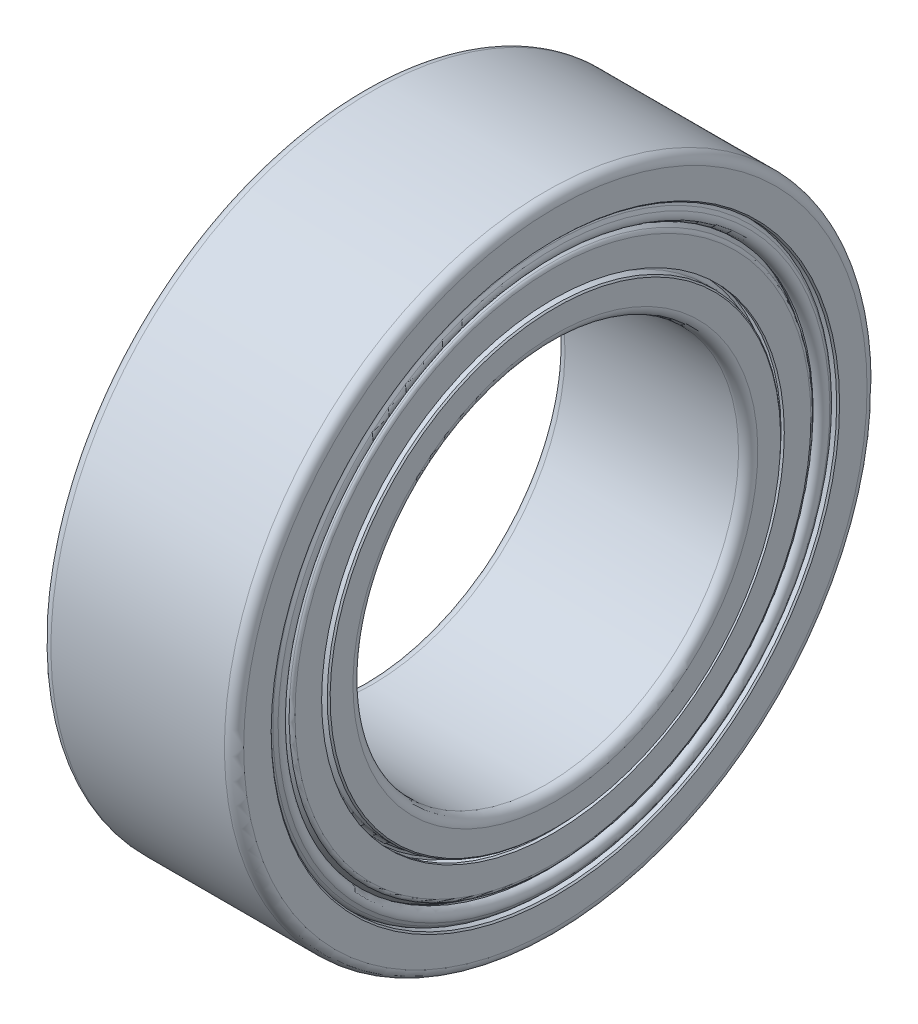
SolidWorks part; units mm, degrees
ref_plane "Front Plane" through (0, 0, 0) normal (0, 0, 1) x (1, 0, 0)
ref_plane "Top Plane" through (0, 0, 0) normal (0, 1, 0) x (1, 0, 0)
ref_plane "Right Plane" through (0, 0, 0) normal (1, 0, 0) x (0, 0, -1)
sketch "Sketch1" plane through (0, 0, 0) normal (1, 0, 0) x (0, 0, -1)
  line L0 (0, 5) -> (0, 4.85) construction
  line L1 (0, 3) -> (0, 3.15) construction
  circle A0 centre (0, 0) radius 5
  circle A1 centre (0, 0) radius 3
  circle A2 centre (0, 0) radius 4.4 construction
  circle A3 centre (0, 0) radius 3.6 construction
  dimension "OD | For Housing ID" = 10
  dimension "ID | For Shaft Diameter" = 6
  dimension "Outer Ring ID" = 8.8
  dimension "Inner Ring OD" = 7.2
  dimension "Radius" = 0.15
sketch "Sketch2" plane through (0, 0, 0) normal (0, 0, 1) x (1, 0, 0)
  line L0 (-1.5, 5) -> (1.5, 5) construction
  point P3 (0, 5)
  dimension "Width" = 3
sketch "Sketch3" plane through (0, 0, 0) normal (0, 0, 1) x (1, 0, 0)
  line L0 (-1.35, 5) -> (1.35, 5)
  line L1 (-1.5, 4.85) -> (-1.5, 4.4225)
  line L2 (1.5, 4.85) -> (1.5, 4.4225)
  line L3 (-1.4775, 4.4) -> (-1.275, 4.4)
  line L4 (-1.4775, 3.5276) -> (-1.5, 3.5051)
  line L5 (-1.3418, 3.5276) -> (-1.4775, 3.5276)
  line L6 (1.5, 4.4225) -> (1.4775, 4.4)
  line L7 (0, 5) -> (0, 4.4) construction
  line L8 (-1.5, 4.4225) -> (-1.4775, 4.4)
  line L9 (1.4775, 3.5276) -> (1.4775, 3.6) construction
  line L10 (-1.2469, 3.6) -> (-1.2469, 3.636)
  line L11 (-1.35, 3) -> (1.35, 3)
  line L12 (-1.5, 3.15) -> (-1.5, 3.5051)
  line L13 (1.5, 3.15) -> (1.5, 3.5051)
  line L14 (-1.2469, 3.6) -> (1.2469, 3.6) construction
  line L15 (1.2469, 3.6) -> (1.2469, 3.45) construction
  line L16 (1.2469, 3.45) -> (1.2469, 3.3) construction
  line L17 (1.2469, 3.6) -> (1.2469, 3.5276) construction
  line L18 (1.2469, 3.5276) -> (1.4775, 3.5276) construction
  line L19 (1.4775, 3.5276) -> (1.5, 3.5051)
  line L20 (1.3418, 3.5276) -> (1.4775, 3.5276)
  line L21 (1.2469, 3.3) -> (1.2469, 3.15) construction
  line L22 (-1.35, 0) -> (1.35, 0) construction
  line L23 (1.275, 4.4) -> (1.275, 4.436)
  line L24 (1.275, 4.436) -> (-1.275, 4.436)
  line L25 (-1.275, 4.4) -> (-1.275, 4.436)
  line L26 (1.275, 4.4) -> (1.4775, 4.4)
  line L27 (-1.2469, 3.636) -> (1.2469, 3.636)
  line L28 (1.2469, 3.636) -> (1.2469, 3.6)
  arc A0 (-1.5, 4.85) -> (-1.35, 5) centre (-1.35, 4.85) cw
  arc A1 (1.35, 5) -> (1.5, 4.85) centre (1.35, 4.85) cw
  arc A2 (-1.5, 3.15) -> (-1.35, 3) centre (-1.35, 3.15) ccw
  arc A3 (1.35, 3) -> (1.5, 3.15) centre (1.35, 3.15) ccw
  arc A4 (1.2469, 3.6) -> (1.3418, 3.5276) centre (1.3418, 3.626) ccw
  arc A5 (-1.2469, 3.6) -> (-1.3418, 3.5276) centre (-1.3418, 3.626) cw
  point P7 (-1.5, 5)
  point P15 (1.5, 5)
  point P30 (0, 3.6)
  point P48 (0, 4.436)
  dimension "D1" = 0.15
  dimension "D4" = 0.15
  dimension "D2" = 135
  dimension "D3" = 0.0225
  dimension "D5" = 135
  dimension "D7" = 0.2531
  dimension "D9" = 0.036
  dimension "D10" = 0.225
  dimension "D8" = 0.0949
  dimension "D6" = 0.0949
revolve "Revolve1" add sketch "Sketch3" angle 360 about L22
sketch "Sketch4" plane through (0, 0, 0) normal (0, 0, 1) x (1, 0, 0)
  line L6 (1.3525, 4.1861) -> (1.33, 4.1991) construction
  line L7 (1.2925, 4.29) -> (1.2925, 4.1601)
  line L8 (1.3, 4.1471) -> (1.4288, 4.0728)
  line L9 (1.4625, 4.0143) -> (1.4625, 3.6)
  line L10 (1.5, -4.85) -> (1.5, 4.85) construction
  line L11 (1.4625, 3.6) -> (1.4025, 3.6) construction
  line L12 (1.4425, 4.238) -> (1.4625, 4.238) construction
  line L15 (1.33, 4.1991) -> (1.3, 4.1471) construction
  line L18 (1.4045, 4.32) -> (1.4345, 4.268)
  line L20 (1.275, 4.4) -> (1.4775, 4.4) construction
  arc A0 (1.2925, 4.29) -> (1.4045, 4.32) centre (1.3525, 4.29) cw
  arc A1 (1.4345, 4.268) -> (1.3525, 4.1861) centre (1.3825, 4.238) cw construction
  arc A2 (1.4288, 4.0728) -> (1.4625, 4.0143) centre (1.395, 4.0143) cw
  arc A3 (1.2925, 4.1601) -> (1.3, 4.1471) centre (1.3075, 4.1601) ccw
  arc A4 (1.4345, 4.268) -> (1.3825, 4.178) centre (1.3825, 4.238) cw
  point P18 (1.2469, 3.6)
  point P28 (1.4625, 4.0533)
  point P31 (1.2925, 4.1514)
  dimension "D8" = 0.0675
  dimension "D9" = 0.015
  dimension "D6" = 0.06
  dimension "D1" = 0.0375
  dimension "D3" = 0.06
  dimension "D2" = 0.06
  dimension "D7" = 30
  dimension "D4" = 120
  dimension "D12" = 0.02
  dimension "D5" = 0.05
revolve "Revolve-Thin1" add sketch "Sketch4" angle 360 about L22
mirror "Mirror2" about plane through (0, 0, 0) normal (1, 0, 0) of bodies 106
delete or keep bodies "Body-Delete/Keep 1" type delete bodies bodies 113
mirror "Mirror1" about plane through (0, 0, 0) normal (1, 0, 0) of bodies 106 112
equation "\"D4@Sketch3\"=\"D1@Sketch3\""
equation "\"D1@Sketch3\"=\"Radius@Sketch1\""
equation "\"D8@Sketch4\"=\"D3@Sketch4\"*1.125"
equation "\"D9@Sketch4\"=\"D3@Sketch4\"*.25"
equation "\"Outer Ring ID@Sketch1\"=\"OD | For Housing ID@Sketch1\"-(((\"OD | For Housing ID@Sketch1\"-\"ID | For Shaft Diameter@Sketch1\")/2)*.3*2)"
equation "\"Inner Ring OD@Sketch1\"=\"ID | For Shaft Diameter@Sketch1\"+(((\"OD | For Housing ID@Sketch1\"-\"ID | For Shaft Diameter@Sketch1\")/2)*.3*2)"
equation "\"Radius@Sketch1\"=\"Width@Sketch2\"*.05"
equation "\"D3@Sketch4\"=\"Width@Sketch2\"*.02"
equation "\"D2@Sketch4\"=\"D3@Sketch4\""
equation "\"D12@Sketch4\"=\"D3@Sketch4\"/3"
equation "\"D6@Sketch4\"=((\"Outer Ring ID@Sketch1\"-\"Inner Ring OD@Sketch1\")/2)*.075"
equation "\"D10@Sketch3\"=\"Width@Sketch2\"*.075"
equation "\"D9@Sketch3\"=((\"OD | For Housing ID@Sketch1\"-\"Outer Ring ID@Sketch1\")/2)*.06"
equation "\"D3@Sketch3\"=\"D9@Sketch3\"*.625"
equation "\"D7@Sketch3\"=\"D10@Sketch3\"*1.125"
equation "\"D6@Sketch3\"=\"D7@Sketch3\"*.375"
equation "\"D8@Sketch3\"=\"D6@Sketch3\""
equation "\"D1@Sketch4\"=\"D3@Sketch4\"*.625"
equation "\"D5@Sketch4\"=((\"Outer Ring ID@Sketch1\"-\"Inner Ring OD@Sketch1\")/2)*.0625"
equation "\"D3@Revolve-Thin1\"=\"D5@Sketch4\""
